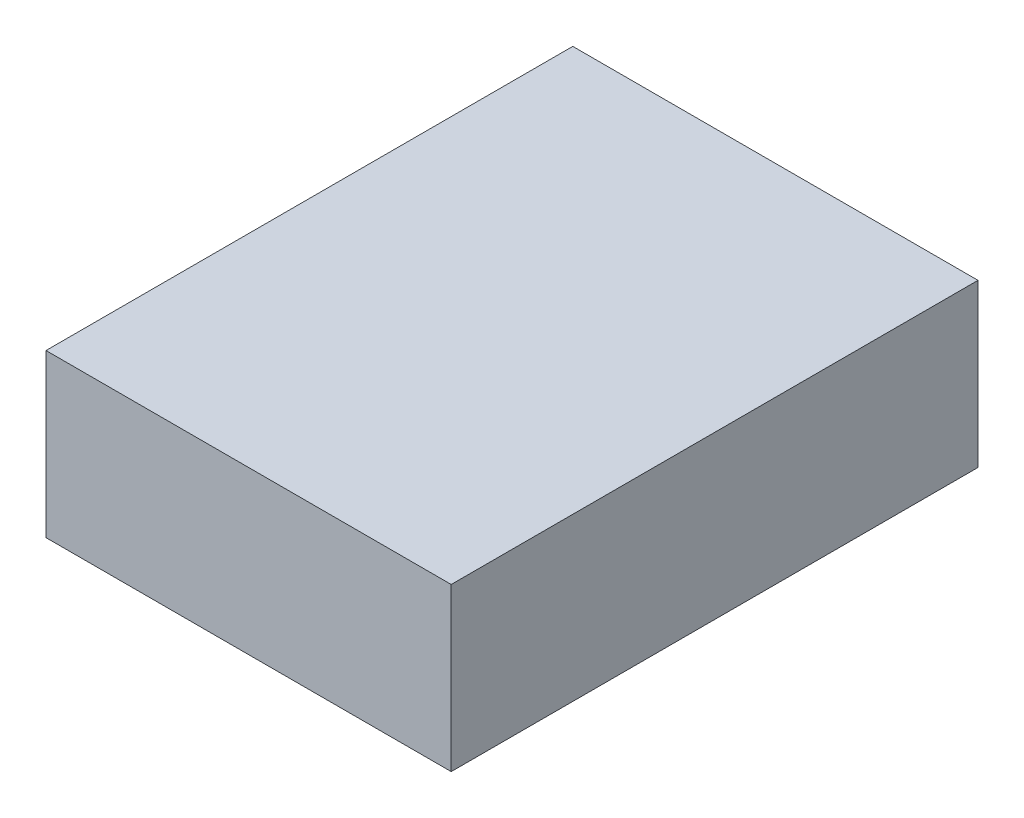
SolidWorks part; units mm, degrees
ref_plane "Спереди" through (0, 0, 0) normal (0, 0, 1) x (1, 0, 0)
ref_plane "Сверху" through (0, 0, 0) normal (0, 1, 0) x (1, 0, 0)
ref_plane "Справа" through (0, 0, 0) normal (1, 0, 0) x (0, 0, -1)
sketch "Sketch1" plane through (0, 0, 0) normal (0, 1, 0) x (1, 0, 0)
  line L1 (-5, -6.5) -> (5, -6.5)
  line L2 (-5, -6.5) -> (-5, 6.5)
  line L3 (-5, 6.5) -> (5, 6.5)
  line L4 (5, -6.5) -> (5, 6.5)
  line L5 (-5, -6.5) -> (5, 6.5) construction
  line L6 (-5, 6.5) -> (5, -6.5) construction
  point P0 (0, 0)
  dimension "D1" = 10
  dimension "D2" = 13
extrude "Boss-Extrude1" add sketch "Sketch1" along normal blind 4
